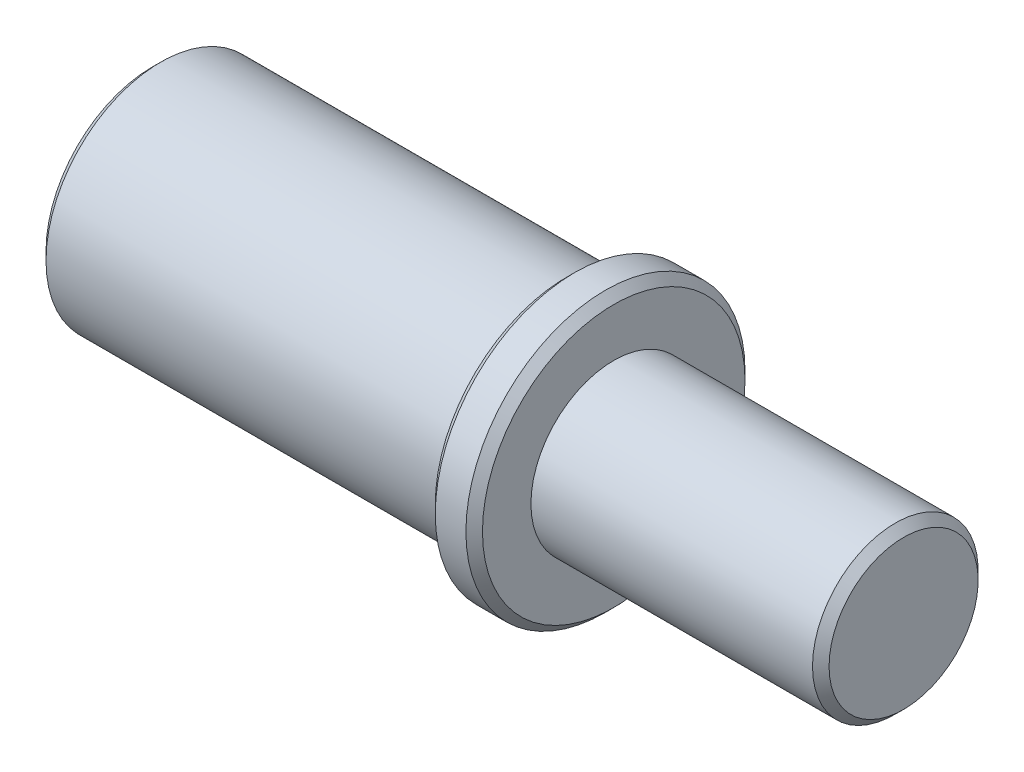
SolidWorks part; units mm, degrees
material "AISI 304"
ref_plane "Спереди" through (0, 0, 0) normal (0, 0, 1) x (1, 0, 0)
ref_plane "Сверху" through (0, 0, 0) normal (0, 1, 0) x (1, 0, 0)
ref_plane "Справа" through (0, 0, 0) normal (1, 0, 0) x (0, 0, -1)
sketch "Эскиз1" plane through (0, 0, 0) normal (0, 0, 1) x (1, 0, 0)
  line L0 (0, 0) -> (130.265, 0) construction
  line L1 (0, 0) -> (0, 13.85)
  line L2 (0, 13.85) -> (50, 13.85)
  line L3 (50, 13.85) -> (50, 16.85)
  line L4 (50, 16.85) -> (55.7, 16.85)
  line L5 (55.7, 16.85) -> (55.7, 10)
  line L6 (55.7, 10) -> (90.7, 10)
  line L7 (90.7, 10) -> (90.7, 0)
  line L8 (90.7, 0) -> (0, 0)
  dimension "D1" = 27.7
  dimension "D2" = 20
  dimension "D3" = 33.7
  dimension "D4" = 5.7
  dimension "D5" = 50
  dimension "D6" = 35
revolve "Повернуть1" add sketch "Эскиз1" angle 360 about L0
chamfer "Фаска1" distance 1 angle 45 4 edges at (0, 0, 13.85) (90.7, 0, 10) (50, 0, 16.85) (55.7, 0, 16.85)
